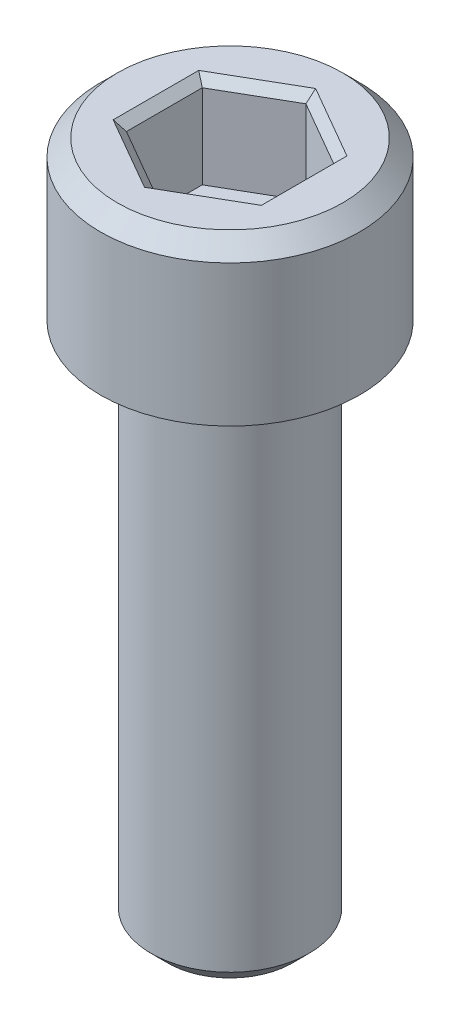
SolidWorks part; units mm, degrees
material "Plain Carbon Steel"
ref_plane "Front Plane" through (0, 0, 0) normal (0, 0, 1) x (1, 0, 0)
ref_plane "Top Plane" through (0, 0, 0) normal (0, 1, 0) x (1, 0, 0)
ref_plane "Right Plane" through (0, 0, 0) normal (1, 0, 0) x (0, 0, -1)
sketch "Sketch1" plane through (0, 0, 0) normal (0, 0, 1) x (1, 0, 0)
  line L0 (-3.9116, -4.7752) -> (0, -4.7752)
  line L1 (0, -4.7752) -> (0, 0)
  line L2 (0, 0) -> (-3.9116, 0)
  line L3 (-3.9116, 0) -> (-3.9116, -4.7752)
  line L4 (0, -4.7752) -> (0, 0) construction
  dimension "D1" = 3.9116
  dimension "D2" = 4.7752
revolve "Revolve1" add sketch "Sketch1" angle 360 about L4
sketch "Sketch2" plane through (0, -4.7752, 0) normal (0, -1, 0) x (1, 0, 0)
  circle A0 centre (0, 0) radius 2.3876
  circle A1 centre (0, 0) radius 3.9116 construction
  dimension "D1" = 4.7752
extrude "Boss-Extrude1" add sketch "Sketch2" along normal blind 15.875
sketch "Sketch3" plane through (0, 0, 0) normal (0, 1, 0) x (-1, 0, 0)
  line L7 (1.9844, -1.1457) -> (1.9844, 1.1457)
  line L8 (1.9844, 1.1457) -> (0, 2.2914)
  line L9 (0, 2.2914) -> (-1.9844, 1.1457)
  line L10 (-1.9844, 1.1457) -> (-1.9844, -1.1457)
  line L11 (-1.9844, -1.1457) -> (0, -2.2914)
  line L12 (0, -2.2914) -> (1.9844, -1.1457)
  circle A0 centre (0, 0) radius 1.9844 construction
  dimension "D1" = 4.5827
extrude "Cut-Extrude1" cut sketch "Sketch3" against normal blind 2.794
chamfer "Chamfer1" distance 0.508 angle 45 2 edges at (0, -20.6502, -2.3876) (0, 0, 3.9116)
chamfer "Chamfer2" distance 0.254 angle 45 6 edges at (-0.9922, 0, 1.7185) (0.9922, 0, 1.7185) (1.9844, 0, 0) (0.9922, 0, -1.7185) (-0.9922, 0, -1.7185) (-1.9844, 0, 0)
